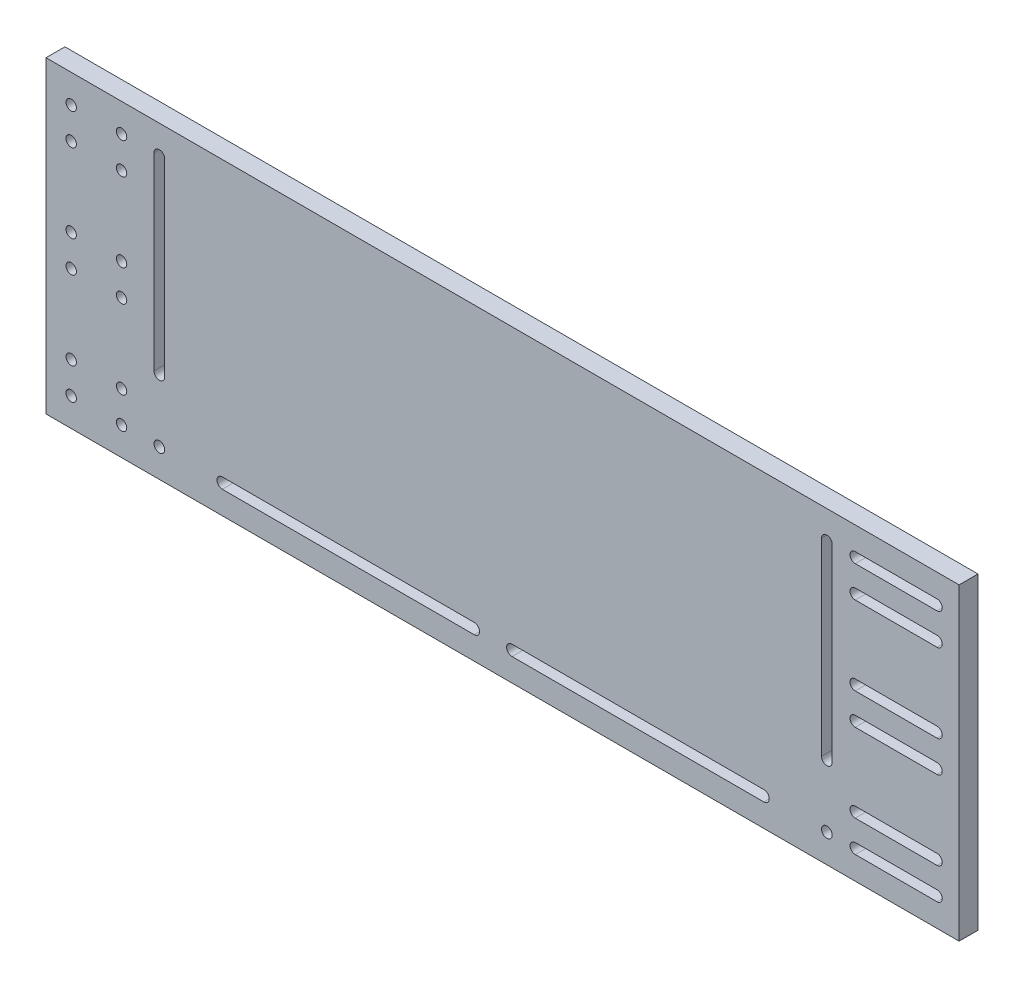
SolidWorks part; units mm, degrees
ref_plane "Front Plane" through (0, 0, 0) normal (0, 0, 1) x (1, 0, 0)
ref_plane "Top Plane" through (0, 0, 0) normal (0, 1, 0) x (1, 0, 0)
ref_plane "Right Plane" through (0, 0, 0) normal (1, 0, 0) x (0, 0, -1)
ref_plane "Plane1" through (0, 0, -9.5) normal (0, 0, -1) x (-1, 0, 0)
sketch "Sketch1" plane through (0, 0, -9.5) normal (0, 0, -1) x (-1, 0, 0)
  line L0 (-11, 71.65) -> (15, 71.65)
  line L1 (15, 68.35) -> (-11, 68.35)
  line L2 (-11, 81.65) -> (15, 81.65)
  line L3 (15, 78.35) -> (-11, 78.35)
  line L4 (15, -1.65) -> (-11, -1.65)
  line L5 (-11, 1.65) -> (15, 1.65)
  line L6 (15, 8.35) -> (-11, 8.35)
  line L7 (-11, 11.65) -> (15, 11.65)
  line L8 (124, -1.7) -> (44, -1.7)
  line L9 (44, 1.7) -> (124, 1.7)
  line L10 (25.7, 80) -> (25.7, 20)
  line L11 (22.3, 20) -> (22.3, 80)
  line L12 (216, -1.7) -> (136, -1.7)
  line L13 (136, 1.7) -> (216, 1.7)
  line L14 (237.7, 80) -> (237.7, 20)
  line L15 (234.3, 20) -> (234.3, 80)
  line L16 (272, -9) -> (272, 89)
  line L17 (272, 89) -> (-18, 89)
  line L18 (-18, 89) -> (-18, -9)
  line L19 (-18, -9) -> (272, -9)
  line L20 (15, 33.3467) -> (-11, 33.3467)
  line L21 (-11, 36.6467) -> (15, 36.6467)
  line L22 (15, 43.3467) -> (-11, 43.3467)
  line L23 (-11, 46.6467) -> (15, 46.6467)
  arc A0 (15, 71.65) -> (15, 68.35) centre (15, 70) cw
  arc A1 (-11, 68.35) -> (-11, 71.65) centre (-11, 70) cw
  arc A2 (15, 81.65) -> (15, 78.35) centre (15, 80) cw
  arc A3 (-11, 78.35) -> (-11, 81.65) centre (-11, 80) cw
  arc A4 (15, 1.65) -> (15, -1.65) centre (15, 0) cw
  arc A5 (-11, -1.65) -> (-11, 1.65) centre (-11, 0) cw
  arc A6 (15, 11.65) -> (15, 8.35) centre (15, 10) cw
  arc A7 (-11, 8.35) -> (-11, 11.65) centre (-11, 10) cw
  circle A8 centre (264, 0) radius 1.65
  circle A9 centre (248, 0) radius 1.65
  circle A10 centre (248, 10) radius 1.65
  circle A11 centre (264, 10) radius 1.65
  circle A12 centre (248, 45.0033) radius 1.65
  circle A13 centre (264, 35.0033) radius 1.65
  circle A14 centre (248, 80) radius 1.65
  circle A15 centre (264, 70) radius 1.65
  arc A16 (124, 1.7) -> (124, -1.7) centre (124, 0) cw
  arc A17 (44, -1.7) -> (44, 1.7) centre (44, 0) cw
  arc A18 (25.7, 20) -> (22.3, 20) centre (24, 20) cw
  arc A19 (22.3, 80) -> (25.7, 80) centre (24, 80) cw
  circle A20 centre (24, 0) radius 1.7
  arc A21 (136, -1.7) -> (136, 1.7) centre (136, 0) cw
  arc A22 (216, 1.7) -> (216, -1.7) centre (216, 0) cw
  arc A23 (237.7, 20) -> (234.3, 20) centre (236, 20) cw
  arc A24 (234.3, 80) -> (237.7, 80) centre (236, 80) cw
  circle A25 centre (236, 0) radius 1.7
  circle A26 centre (248, 70) radius 1.65
  circle A27 centre (264, 80) radius 1.65
  circle A28 centre (248, 35.0033) radius 1.65
  circle A29 centre (264, 45.0033) radius 1.65
  arc A30 (15, 36.6467) -> (15, 33.3467) centre (15, 34.9967) cw
  arc A31 (-11, 33.3467) -> (-11, 36.6467) centre (-11, 34.9967) cw
  arc A32 (15, 46.6467) -> (15, 43.3467) centre (15, 44.9967) cw
  arc A33 (-11, 43.3467) -> (-11, 46.6467) centre (-11, 44.9967) cw
extrude "Boss-Extrude1" add sketch "Sketch1" against normal blind 6
